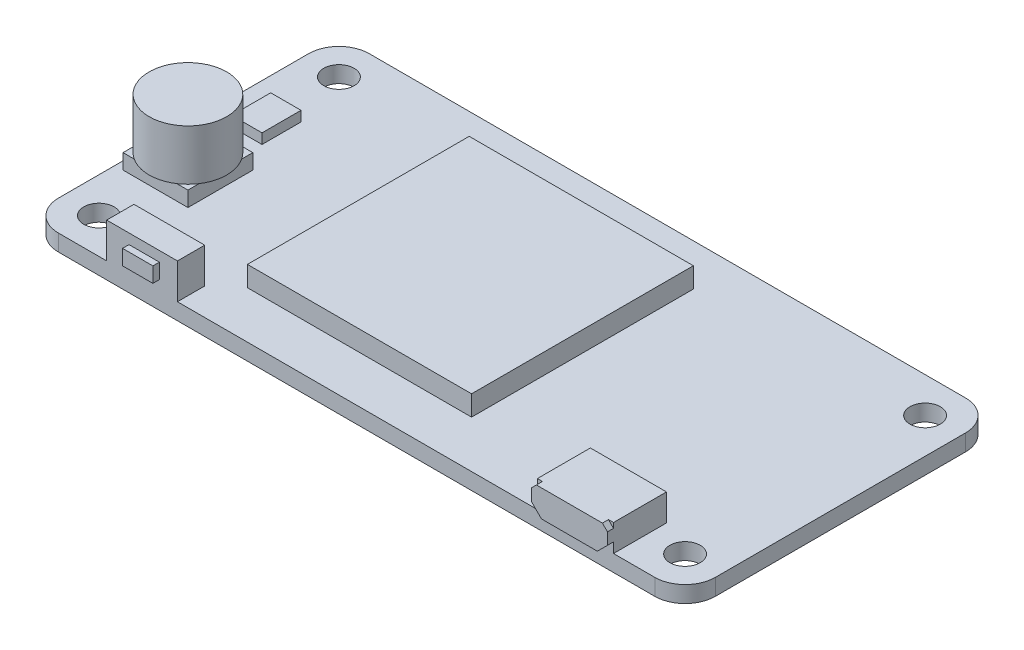
SolidWorks part; units mm, degrees
ref_plane "前视基准面" through (0, 0, 0) normal (0, 0, 1) x (1, 0, 0)
ref_plane "上视基准面" through (0, 0, 0) normal (0, 1, 0) x (1, 0, 0)
ref_plane "右视基准面" through (0, 0, 0) normal (1, 0, 0) x (0, 0, -1)
sketch "草图1" plane through (0, 0, 0) normal (0, 1, 0) x (1, 0, 0)
  line L1 (-29.5, 15.375) -> (29.5, 15.375)
  line L2 (-32.5, 12.375) -> (-32.5, -12.375)
  line L3 (-29.5, -15.375) -> (29.5, -15.375)
  line L4 (32.5, 12.375) -> (32.5, -12.375)
  line L5 (-32.5, 15.375) -> (32.5, -15.375) construction
  line L6 (-32.5, -15.375) -> (32.5, 15.375) construction
  arc A0 (-32.5, -12.375) -> (-29.5, -15.375) centre (-29.5, -12.375) ccw
  arc A1 (29.5, -15.375) -> (32.5, -12.375) centre (29.5, -12.375) ccw
  arc A2 (29.5, 15.375) -> (32.5, 12.375) centre (29.5, 12.375) cw
  arc A3 (-29.5, 15.375) -> (-32.5, 12.375) centre (-29.5, 12.375) ccw
  point P0 (0, 0)
  dimension "D3" = 3
  dimension "D1" = 30.75
  dimension "D2" = 65
extrude "凸台-拉伸1" add sketch "草图1" along normal blind 1.63
sketch "草图2" plane through (0, 1.63, 0) normal (0, 1, 0) x (1, 0, 0)
  line L0 (29.5, 15.375) -> (-29.5, 15.375) construction
  line L2 (-32.5, 12.375) -> (-32.5, -12.375) construction
  line L3 (-29.5, -15.375) -> (29.5, -15.375) construction
  line L4 (32.5, -12.375) -> (32.5, 12.375) construction
  circle A0 centre (-29, 11.875) radius 1.5
  circle A1 centre (-29, -11.875) radius 1.5
  circle A2 centre (29, -11.875) radius 1.5
  circle A3 centre (29, 11.875) radius 1.5
  dimension "D1" = 3
  dimension "D2" = 3.5
  dimension "D3" = 3.5
  dimension "D4" = 3.5
  dimension "D5" = 3.5
extrude "切除-拉伸1" cut sketch "草图2" against normal through all
sketch "草图8" plane through (0, 0, 0) normal (0, -1, 0) x (1, 0, 0)
  line L0 (29.5, -15.375) -> (-29.5, -15.375) construction
  line L1 (-25.7, -8.735) -> (25.3, -8.735)
  line L2 (-25.7, -8.735) -> (-25.7, -13.735)
  line L3 (-25.7, -13.735) -> (25.3, -13.735)
  line L4 (25.3, -8.735) -> (25.3, -13.735)
  line L5 (32.5, 12.375) -> (32.5, -12.375) construction
  dimension "D1" = 5
  dimension "D2" = 51
  dimension "D3" = 1.64
  dimension "D4" = 7.2
extrude "凸台-拉伸6" add sketch "草图8" along normal blind 3.68
sketch "草图9" plane through (0, 1.63, 0) normal (0, 1, 0) x (1, 0, 0)
  line L0 (-29.5, -15.375) -> (29.5, -15.375) construction
  line L1 (-24.73, -15.375) -> (-17.73, -15.375)
  line L2 (-24.73, -15.375) -> (-24.73, -12.675)
  line L3 (-24.73, -12.675) -> (-17.73, -12.675)
  line L4 (-17.73, -15.375) -> (-17.73, -12.675)
  line L5 (-32.5, 12.375) -> (-32.5, -12.375) construction
  dimension "D1" = 7
  dimension "D2" = 7.77
  dimension "D3" = 2.7
extrude "凸台-拉伸7" add sketch "草图9" along normal blind 3.5
sketch "草图10" plane through (0, 1.63, 0) normal (0, 1, 0) x (1, 0, 0)
  line L0 (-17.73, -15.375) -> (29.5, -15.375) construction
  line L1 (17.89, -10.135) -> (25.42, -10.135)
  line L2 (17.89, -10.135) -> (17.89, -15.375)
  line L3 (17.89, -15.375) -> (25.42, -15.375)
  line L4 (25.42, -10.135) -> (25.42, -15.375)
  line L5 (32.5, -12.375) -> (32.5, 12.375) construction
  dimension "D1" = 7.53
  dimension "D2" = 5.24
  dimension "D3" = 7.08
extrude "凸台-拉伸8" add sketch "草图10" along normal blind 2.66
sketch "草图11" plane through (0, 1.63, 0) normal (0, 1, 0) x (1, 0, 0)
  line L0 (29.5, 15.375) -> (-29.5, 15.375) construction
  line L1 (-15.47, 11.235) -> (6.71, 11.235)
  line L2 (-15.47, 11.235) -> (-15.47, -10.7107)
  line L3 (-15.47, -10.7107) -> (6.71, -10.7107)
  line L4 (6.71, 11.235) -> (6.71, -10.7107)
  line L5 (-32.5, 12.375) -> (-32.5, -12.375) construction
  dimension "D1" = 22.18
  dimension "D2" = 4.14
  dimension "D3" = 17.03
extrude "凸台-拉伸9" add sketch "草图11" along normal blind 2
sketch "草图12" plane through (0, 1.63, 0) normal (0, 1, 0) x (1, 0, 0)
  line L0 (-29.5, -15.375) -> (-24.73, -15.375) construction
  line L1 (-31.7, -0.365) -> (-25.28, -0.365)
  line L2 (-31.7, -0.365) -> (-31.7, -6.785)
  line L3 (-31.7, -6.785) -> (-25.28, -6.785)
  line L4 (-25.28, -0.365) -> (-25.28, -6.785)
  line L5 (-32.5, 12.375) -> (-32.5, -12.375) construction
  dimension "D1" = 8.59
  dimension "D2" = 6.42
  dimension "D3" = 6.42
  dimension "D4" = 0.8
extrude "凸台-拉伸10" add sketch "草图12" along normal blind 1.5
sketch "草图13" plane through (0, 1.63, 0) normal (0, 1, 0) x (1, 0, 0)
  line L0 (29.5, 15.375) -> (-29.5, 15.375) construction
  line L1 (-30.02, 6.145) -> (-27.02, 6.145)
  line L2 (-30.02, 6.145) -> (-30.02, 2.285)
  line L3 (-30.02, 2.285) -> (-27.02, 2.285)
  line L4 (-27.02, 6.145) -> (-27.02, 2.285)
  line L5 (-32.5, 12.375) -> (-32.5, -12.375) construction
  dimension "D1" = 3.86
  dimension "D2" = 3
  dimension "D3" = 9.23
  dimension "D4" = 2.48
extrude "凸台-拉伸11" add sketch "草图13" along normal blind 1
sketch "草图14" plane through (0, 3.13, 0) normal (0, 1, 0) x (1, 0, 0)
  circle A0 centre (-28.49, -3.575) radius 3.84
  dimension "D1" = 7.68
extrude "凸台-拉伸12" add sketch "草图14" along normal blind 5 contours A0
sketch "草图15" plane through (0, 0, 15.375) normal (0, 0, 1) x (1, 0, 0)
  line L0 (-24.73, 5.13) -> (-24.73, 1.63) construction
  line L1 (-22.52, 4.13) -> (-19.52, 4.13)
  line L2 (-22.52, 4.13) -> (-22.52, 2.63)
  line L3 (-22.52, 2.63) -> (-19.52, 2.63)
  line L4 (-19.52, 4.13) -> (-19.52, 2.63)
  line L5 (-24.73, 5.13) -> (-17.73, 5.13) construction
  dimension "D1" = 3
  dimension "D2" = 1.5
  dimension "D3" = 2.21
  dimension "D4" = 1
extrude "凸台-拉伸13" add sketch "草图15" along normal blind 0.64
sketch "草图16" plane through (0, 0, 15.375) normal (0, 0, 1) x (1, 0, 0)
  line L0 (17.89, 3.79) -> (18.39, 4.29)
  line L1 (18.39, 4.29) -> (24.92, 4.29)
  line L2 (17.89, 3.79) -> (17.89, 2.63)
  line L3 (18.89, 1.63) -> (24.42, 1.63)
  line L4 (25.42, 3.79) -> (25.42, 2.63)
  line L5 (24.92, 4.29) -> (25.42, 3.79)
  line L6 (17.89, 2.63) -> (18.89, 1.63)
  line L7 (24.42, 1.63) -> (25.42, 2.63)
  point P0 (17.89, 4.29)
  point P1 (25.42, 1.63)
  point P2 (17.89, 1.63)
  point P3 (25.42, 4.29)
extrude "凸台-拉伸14" add sketch "草图16" along normal blind 0.6
